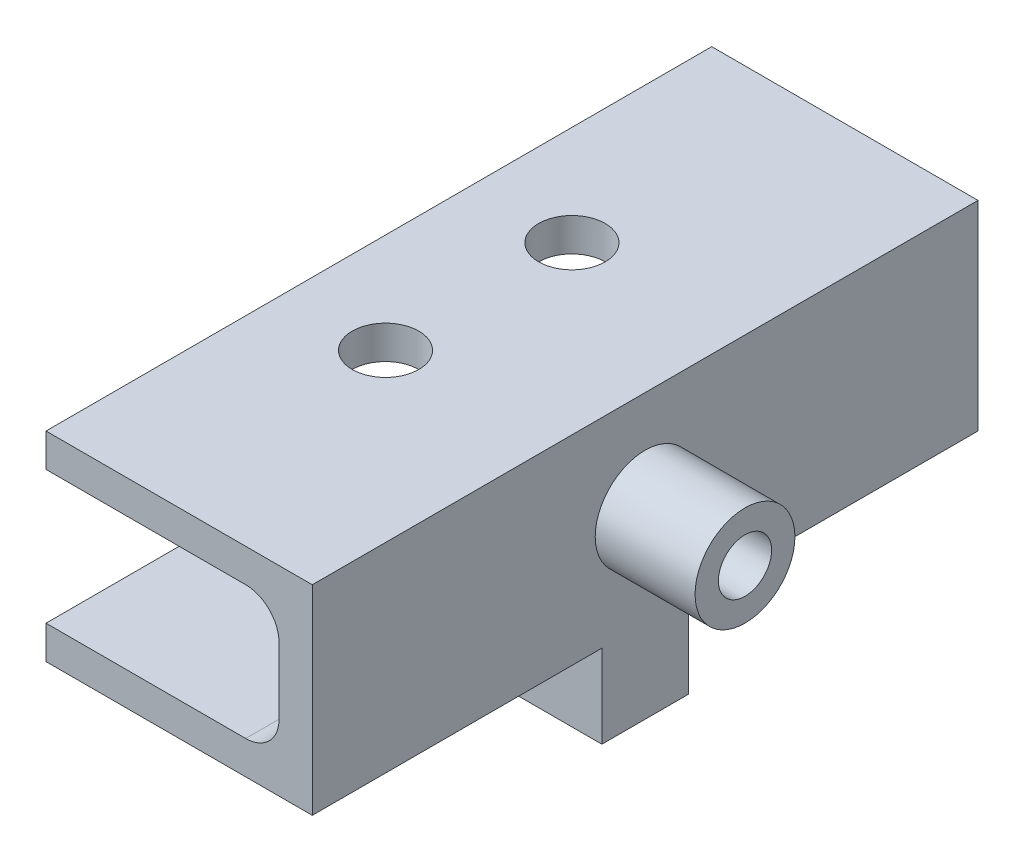
SolidWorks part; units mm, degrees
ref_plane "Front Plane" through (0, 0, 0) normal (0, 0, 1) x (1, 0, 0)
ref_plane "Top Plane" through (0, 0, 0) normal (0, 1, 0) x (1, 0, 0)
ref_plane "Right Plane" through (0, 0, 0) normal (1, 0, 0) x (0, 0, -1)
sketch "Sketch1" plane through (0, 0, 0) normal (0, 0, 1) x (1, 0, 0)
  line L0 (0, 0) -> (35, 0)
  line L1 (35, 0) -> (35, -20)
  line L2 (35, -20) -> (0, -20)
  line L3 (0, -20) -> (0, -25)
  line L4 (0, -25) -> (40, -25)
  line L5 (40, -25) -> (40, 5)
  line L6 (40, 5) -> (0, 5)
  line L7 (0, 5) -> (0, 0)
  dimension "D1" = 5
  dimension "D2" = 5
  dimension "D3" = 5
  dimension "D4" = 35
  dimension "D5" = 20
extrude "Boss-Extrude1" add sketch "Sketch1" along normal blind 100
fillet "Fillet1" radius 5 2 edges at (35, -20, 50) (35, 0, 50)
sketch "Sketch2" plane through (0, 5, 0) normal (0, 1, 0) x (1, 0, 0)
  line L0 (0, -50) -> (40, -50) construction
  line L1 (0, -100) -> (0, 0) construction
  line L2 (40, -100) -> (40, 0) construction
  circle A0 centre (15, -64) radius 5
  circle A2 centre (15, -36) radius 5
  dimension "D1" = 14
  dimension "D2" = 10
  dimension "D3" = 15
extrude "Cut-Extrude1" cut sketch "Sketch2" against normal blind 75 contours A0 | A2
sketch "Sketch3" plane through (0, -25, 0) normal (0, -1, 0) x (1, 0, 0)
  line L7 (0, 43.5) -> (40, 43.5)
  line L8 (0, 43.5) -> (0, 56.5)
  line L9 (0, 56.5) -> (40, 56.5)
  line L10 (40, 43.5) -> (40, 56.5)
  line L12 (40, 100) -> (40, 0) construction
  circle A0 centre (15, 36) radius 5 construction
  dimension "D1" = 13
  dimension "D2" = 7.5
  dimension "D3" = 40
  dimension "D4" = 0
extrude "Boss-Extrude2" add sketch "Sketch3" along normal blind 12.5
sketch "Sketch9" plane through (40, 0, 0) normal (1, 0, 0) x (0, 0, -1)
  line L0 (0, -25) -> (0, 5) construction
  line L1 (-100, -25) -> (-56.5, -25) construction
  circle A0 centre (-50, -10) radius 7.5
  dimension "D1" = 50
  dimension "D2" = 15
extrude "Boss-Extrude6" add sketch "Sketch9" along normal blind 15
sketch "Sketch10" plane through (55, 0, 0) normal (1, 0, 0) x (0, 0, -1)
  circle A0 centre (-50, -10) radius 4
extrude "Cut-Extrude3" cut sketch "Sketch10" against normal blind 15
